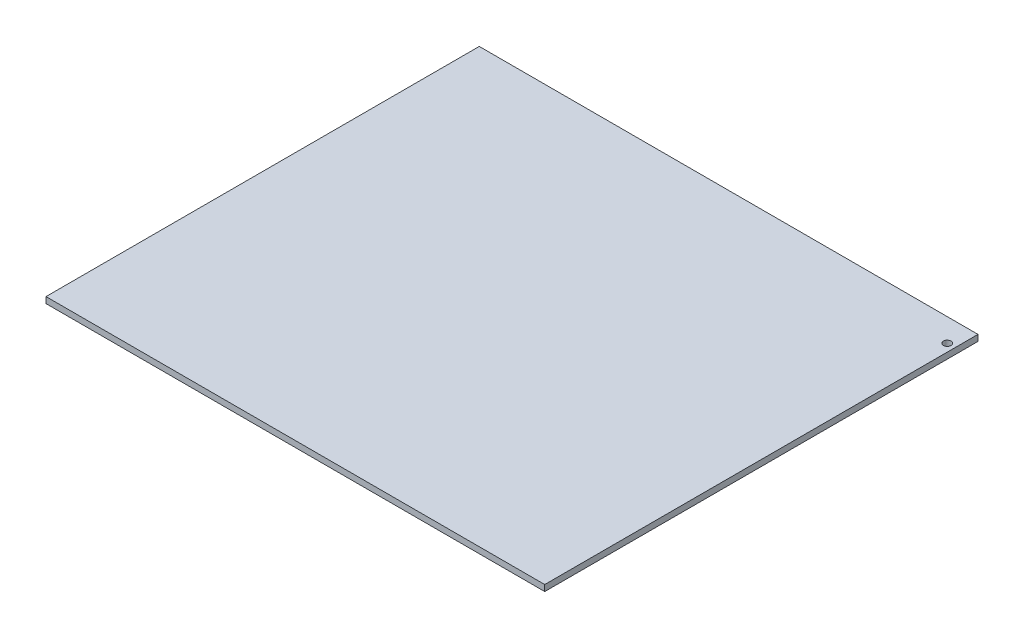
SolidWorks part; units mm, degrees
ref_plane "Front Plane" through (0, 0, 0) normal (0, 0, 1) x (1, 0, 0)
ref_plane "Top Plane" through (0, 0, 0) normal (0, 1, 0) x (1, 0, 0)
ref_plane "Right Plane" through (0, 0, 0) normal (1, 0, 0) x (0, 0, -1)
sketch "Sketch1" plane through (0, 0, 0) normal (0, 1, 0) x (1, 0, 0)
  line L1 (-129.5, 112.5) -> (129.5, 112.5)
  line L2 (-129.5, 112.5) -> (-129.5, -112.5)
  line L3 (-129.5, -112.5) -> (129.5, -112.5)
  line L4 (129.5, 112.5) -> (129.5, -112.5)
  line L5 (-129.5, 112.5) -> (129.5, -112.5) construction
  line L6 (-129.5, -112.5) -> (129.5, 112.5) construction
  point P0 (0, 0)
  dimension "D1" = 259
  dimension "D2" = 225
extrude "Boss-Extrude1" add sketch "Sketch1" along normal blind 3.175
sketch "Existing dims" plane through (0, 3.175, 0) normal (0, 1, 0) x (1, 0, 0)
  line L0 (129.5, -112.5) -> (129.5, 112.5) construction
  line L1 (129.5, 112.5) -> (-129.5, 112.5) construction
  line L2 (129.5, 112.5) -> (129.5, -4.5) construction
  line L3 (129.5, -4.5) -> (-129.5, -4.5) construction
  line L4 (-129.5, 112.5) -> (-129.5, -112.5) construction
  line L5 (-129.5, 112.5) -> (-129.5, 29.5) construction
  line L6 (-129.5, 29.5) -> (129.5, 29.5)
  circle A0 centre (80.5, 98) radius 1.5
  dimension "D1" = 49
  dimension "D2" = 3
  dimension "D3" = 14.5
  dimension "D4" = 117
  dimension "D5" = 83
sketch "New mounting hole" plane through (0, 3.175, 0) normal (0, 1, 0) x (1, 0, 0)
  line L0 (129.5, 112.5) -> (129.5, -4.5) construction
  line L1 (129.5, 112.5) -> (-129.5, 112.5) construction
  circle A0 centre (125.5, 100.5) radius 2
  dimension "D1" = 4
  dimension "D2" = 4
  dimension "D3" = 12
extrude "New mount hole" cut sketch "New mounting hole" against normal mid plane 10
sketch "Sketch5" plane through (0, 3.175, 0) normal (0, 1, 0) x (1, 0, 0)
  line L0 (129.5, -112.5) -> (101.5, -112.5) construction
  line L1 (101.5, -112.5) -> (101.5, 112.5) construction
  line L2 (129.5, 112.5) -> (-129.5, 112.5) construction
  dimension "D1" = 28
